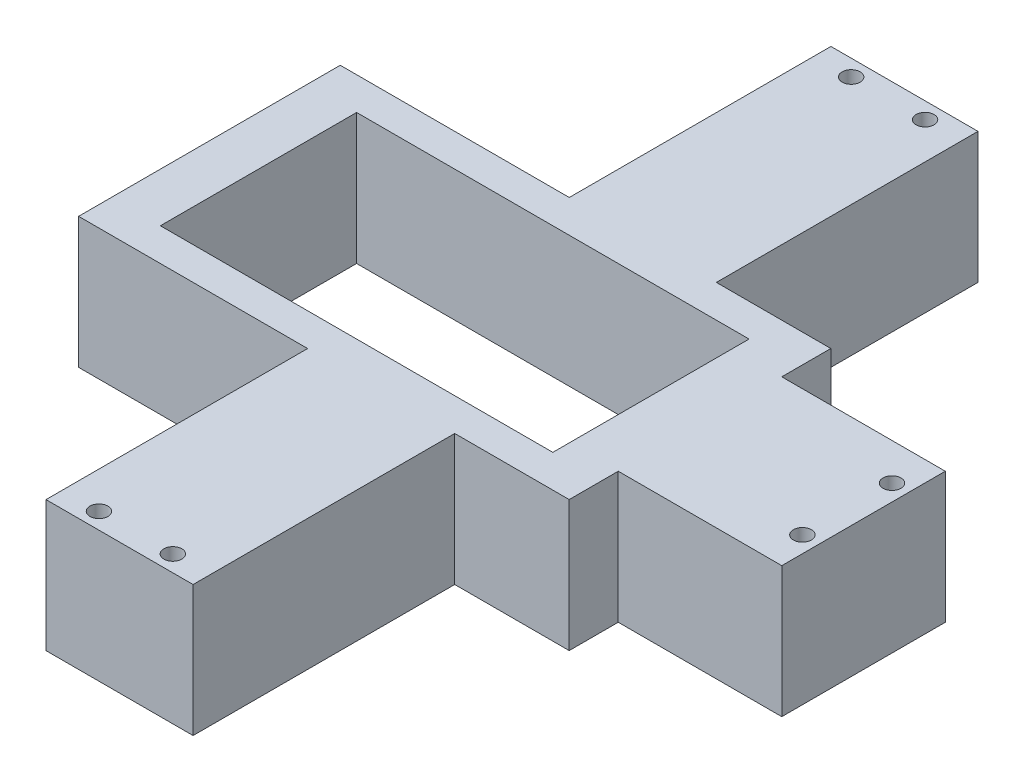
SolidWorks part; units mm, degrees
ref_plane "Front Plane" through (0, 0, 0) normal (0, 0, 1) x (1, 0, 0)
ref_plane "Top Plane" through (0, 0, 0) normal (0, 1, 0) x (1, 0, 0)
ref_plane "Right Plane" through (0, 0, 0) normal (1, 0, 0) x (0, 0, -1)
sketch "Sketch2" plane through (0, 0, 0) normal (0, 1, 0) x (1, 0, 0)
  line L0 (57.5, 0) -> (57.5, -40)
  line L1 (35.013, 80) -> (57.5, 80)
  line L2 (35.013, 80) -> (35.013, 40)
  line L3 (35.013, -40) -> (57.5, -40)
  line L4 (57.5, 80) -> (57.5, 40)
  line L5 (0, 40) -> (35.013, 40)
  line L6 (0, 40) -> (0, 0)
  line L7 (0, 0) -> (35.013, 0)
  line L8 (75, 40) -> (75, 32.5)
  line L9 (75, 32.5) -> (100, 32.5)
  line L11 (75, 7.5) -> (100, 7.5)
  line L12 (100, 32.5) -> (100, 7.5)
  line L13 (35.013, 0) -> (35.013, -40)
  line L14 (57.5, 40) -> (75, 40)
  line L15 (57.5, 0) -> (75, 0)
  line L16 (75, 7.5) -> (75, 0)
  line L17 (35.013, 0) -> (57.5, 0)
  point P16 (0, 0)
  dimension "D1" = 120
  dimension "D2" = 40
  dimension "D3" = 75
  dimension "D4" = 100
  dimension "D5" = 7.5
  dimension "D6" = 17.5
  dimension "D7" = 22.487
extrude "Boss-Extrude1" add sketch "Sketch2" along normal blind 20 contours L8 L9 L12 L11 L16 L15 L0 L3 L13 L7 L6 L5 L2 L1 L4 L14
sketch "Sketch3" plane through (0, 20, 0) normal (0, 1, 0) x (1, 0, 0)
  line L0 (0, 0) -> (35.013, 0) construction
  line L1 (7.5, 35) -> (67.5, 35)
  line L2 (7.5, 35) -> (7.5, 5)
  line L3 (7.5, 5) -> (67.5, 5)
  line L4 (67.5, 35) -> (67.5, 5)
  line L6 (0, 40) -> (0, 0) construction
  dimension "D1" = 60
  dimension "D2" = 30
  dimension "D3" = 5
  dimension "D4" = 7.5
extrude "Cut-Extrude1" cut sketch "Sketch3" against normal up to next
sketch "Sketch11" plane through (0, 20, 0) normal (0, 1, 0) x (1, 0, 0)
  line L0 (57.5, -40) -> (57.5, -35)
  line L1 (57.5, 0) -> (57.5, -40) construction
  line L2 (100, 32.5) -> (95, 32.5)
  line L3 (75, 32.5) -> (100, 32.5) construction
  line L4 (95, 32.5) -> (95, 7.5) construction
  line L5 (75, 7.5) -> (100, 7.5) construction
  line L6 (35.013, 80) -> (35.013, 75) construction
  line L7 (35.013, 80) -> (35.013, 40) construction
  line L8 (35.013, 75) -> (57.5, 75) construction
  line L9 (57.5, 80) -> (57.5, 40) construction
  line L10 (57.5, -35) -> (35.013, -35) construction
  line L11 (35.013, 0) -> (35.013, -40) construction
  line L13 (57.5, -37.5) -> (35.013, -37.5) construction
  line L14 (97.5, 32.5) -> (97.5, 7.5) construction
  line L17 (35.013, 77.5) -> (57.5, 77.5) construction
  line L19 (40.6065, -37.5) -> (40.6065, 77.5) construction
  line L21 (51.9065, -37.5) -> (51.9065, 77.5) construction
  line L23 (35.013, 80) -> (57.5, 80) construction
  line L24 (100, 32.5) -> (100, 7.5) construction
  point P39 (40.6065, -37.5)
  point P41 (51.9065, -37.5)
  point P43 (97.5, 13.15)
  point P45 (97.5, 26.85)
  point P47 (40.6065, 77.5)
  point P49 (51.9065, 77.5)
  point P66 (46.2565, -37.5)
  point P67 (0, 0)
  point P68 (0, 0)
  point P69 (0, 0)
  point P71 (0, 0)
  dimension "D1" = 5.65
  dimension "D2" = 5.65
  dimension "D3" = 5.65
  dimension "D4" = 5.65
  dimension "D5" = 5
  dimension "D6" = 5
  dimension "D7" = 5
hole_wizard "Ø1.0mm Dowel Hole4" positions "Sketch11" profile "Sketch13" hole size "Ø1.0" standard "ANSI Metric"
sketch "Sketch13" plane through (51.9065, 20, -77.5) normal (1, 0, 0) x (0, 0, 1)
  line L0 (0, 0) -> (0, 10.8262)
  line L1 (0, 10.8262) -> (1.375, 10)
  line L2 (1.375, 10) -> (1.375, 0)
  line L5 (1.375, 0) -> (0, 0)
  line L10 (0, 10.8262) -> (-1.375, 10) construction
  line L11 (0, -6.35) -> (0, 107.95) construction
  dimension "Hole Dia." = 2.75
  dimension "Hole Depth" = 10
  dimension "Drill Angle" = 118
